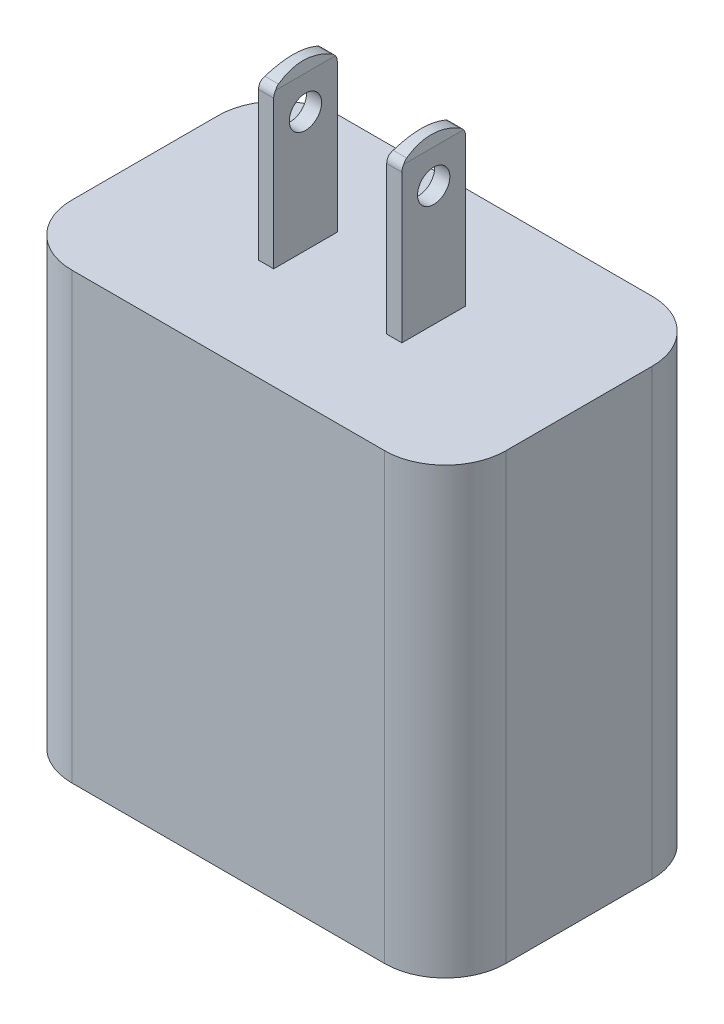
SolidWorks part; units mm, degrees
ref_plane "Front Plane" through (0, 0, 0) normal (0, 0, 1) x (1, 0, 0)
ref_plane "Top Plane" through (0, 0, 0) normal (0, 1, 0) x (1, 0, 0)
ref_plane "Right Plane" through (0, 0, 0) normal (1, 0, 0) x (0, 0, -1)
sketch "Sketch2" plane through (0, 0, 0) normal (0, 1, 0) x (1, 0, 0)
  line L1 (-21.5, -13.25) -> (21.5, -13.25)
  line L2 (-21.5, -13.25) -> (-21.5, 13.25)
  line L3 (-21.5, 13.25) -> (21.5, 13.25)
  line L4 (21.5, -13.25) -> (21.5, 13.25)
  line L5 (-21.5, -13.25) -> (21.5, 13.25) construction
  line L6 (-21.5, 13.25) -> (21.5, -13.25) construction
  point P0 (0, 0)
  dimension "D1" = 26.5
  dimension "D2" = 43
extrude "Boss-Extrude1" add sketch "Sketch2" along normal blind 44
sketch "Sketch3" plane through (0, 0, 0) normal (0, -1, 0) x (1, 0, 0)
  line L1 (-6.1, -2.4) -> (6.1, -2.4)
  line L2 (-6.1, -2.4) -> (-6.1, 2.4)
  line L3 (-6.1, 2.4) -> (6.1, 2.4)
  line L4 (6.1, -2.4) -> (6.1, 2.4)
  line L5 (-6.1, -2.4) -> (6.1, 2.4) construction
  line L6 (-6.1, 2.4) -> (6.1, -2.4) construction
  point P0 (0, 0)
  dimension "D1" = 4.8
  dimension "D2" = 12.2
extrude "Cut-Extrude1" cut sketch "Sketch3" against normal blind 10
sketch "Sketch4" plane through (0, 44, 0) normal (0, 1, 0) x (1, 0, 0)
  line L2 (-5.6, -3.15) -> (-5.6, 3.15)
  line L4 (5.6, -3.15) -> (5.6, 3.15)
  line L7 (5.6, 3.15) -> (7.1, 3.15)
  line L8 (5.6, 3.15) -> (5.6, -3.15)
  line L9 (5.6, -3.15) -> (7.1, -3.15)
  line L10 (7.1, 3.15) -> (7.1, -3.15)
  line L11 (-5.6, 3.15) -> (-7.1, 3.15)
  line L12 (-5.6, 3.15) -> (-5.6, -3.15)
  line L13 (-5.6, -3.15) -> (-7.1, -3.15)
  line L14 (-7.1, 3.15) -> (-7.1, -3.15)
  point P0 (0, 0)
  dimension "D1" = 6.3
  dimension "D2" = 11.2
  dimension "D3" = 6.3
  dimension "D4" = 1.5
  dimension "D5" = 6.3
  dimension "D6" = 1.5
extrude "Boss-Extrude2" add sketch "Sketch4" along normal blind 16.2 contours L11 L14 L13 L2 | L10 L7 L4 L9
sketch "Sketch5" plane through (7.1, 0, 0) normal (1, 0, 0) x (0, 0, -1)
  line L0 (0, 23.65) -> (0, -23.65) construction
  line L1 (3.15, 60.2) -> (-3.15, 60.2) construction
  circle A0 centre (0, 55.9) radius 1.6
  dimension "D1" = 3.2
  dimension "D2" = 4.3
extrude "Cut-Extrude2" cut sketch "Sketch5" against normal blind 16.2
sketch "Sketch6" plane through (0, 0, -3.15) normal (0, 0, -1) x (-1, 0, 0)
  line L0 (-6.85, 60.2) -> (-5.85, 60.2)
  line L1 (-5.6, 60.2) -> (-7.1, 60.2) construction
  line L2 (-5.85, 60.2) -> (-5.6, 59.2318)
  line L3 (-5.6, 60.2) -> (-5.6, 44) construction
  line L4 (-5.6, 59.2318) -> (-5.6, 60.385)
  line L5 (-5.6, 60.385) -> (-7.1, 60.385)
  line L6 (-7.1, 60.385) -> (-7.1, 59.2318)
  line L7 (-7.1, 60.2) -> (-7.1, 44) construction
  line L8 (-7.1, 59.2318) -> (-6.85, 60.2)
  point P5 (-6.35, 60.2)
  dimension "D1" = 1
extrude "Cut-Extrude3" cut sketch "Sketch6" against normal blind 16.2
mirror "Mirror1" about plane through (0, 0, 0) normal (1, 0, 0) of "Cut-Extrude3"
sketch "Sketch7" plane through (7.1, 0, 0) normal (1, 0, 0) x (0, 0, -1)
  line L1 (-3.15, 59.2318) -> (0, 61.1218) construction
  line L2 (0, 61.1218) -> (3.15, 59.2318) construction
  line L5 (0, 23.65) -> (0, -23.65) construction
  line L7 (-3.15, 59.2318) -> (-3.15, 61.2071)
  line L8 (-3.15, 61.2071) -> (3.15, 61.2071)
  line L9 (3.15, 61.2071) -> (3.15, 59.2318)
  spline S0 degree 2 poles (-3.15, 59.2318) (0, 61.1218) (3.15, 59.2318) knots 0 0 0 1 1 1
extrude "Cut-Extrude4" cut sketch "Sketch7" against normal blind 16.2
fillet "Fillet1" radius 1 4 edges at (6.35, 59.2318, -3.15) (-6.35, 59.2318, -3.15) (-6.35, 59.2318, 3.15) (6.35, 59.2318, 3.15)
fillet "Fillet2" radius 6 4 edges at (21.5, 22, 13.25) (-21.5, 22, 13.25) (-21.5, 22, -13.25) (21.5, 22, -13.25)
sketch "Sketch8" plane through (0, 10, 0) normal (0, -1, 0) x (1, 0, 0)
  line L0 (-6.1, -2.4) -> (6.1, -2.4) construction
  line L1 (-5.1, 1.7) -> (5.1, 1.7)
  line L2 (-5.1, 1.7) -> (-5.1, 0.2)
  line L3 (-5.1, 0.2) -> (5.1, 0.2)
  line L4 (5.1, 1.7) -> (5.1, 0.2)
  line L5 (-6.1, 2.4) -> (-6.1, -2.4) construction
  line L6 (6.1, -2.4) -> (6.1, 2.4) construction
  dimension "D1" = 2.6
  dimension "D2" = 1.5
  dimension "D3" = 1
  dimension "D4" = 1
extrude "Boss-Extrude3" add sketch "Sketch8" along normal offset from surface (9 mm away) 1 up to face at (0, 0, 0)
chamfer "Chamfer1" distance 0.4 angle 45 4 edges at (5.1, 1, 0.95) (0, 1, 0.2) (-5.1, 1, 0.95) (0, 1, 1.7)
